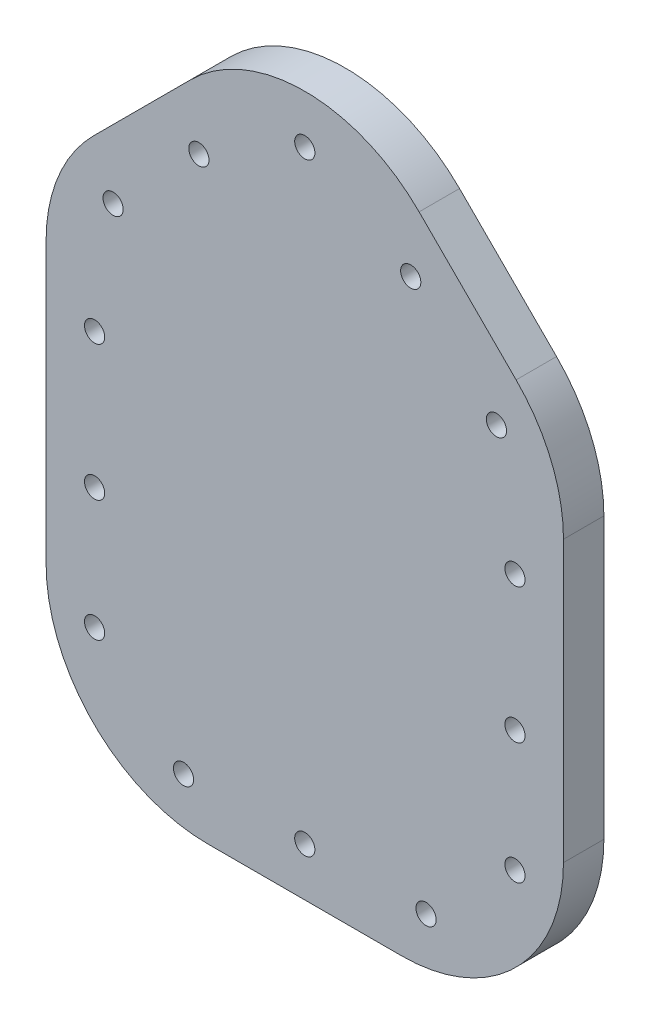
SolidWorks part; units mm, degrees
ref_plane "Front Plane" through (0, 0, 0) normal (0, 0, 1) x (1, 0, 0)
ref_plane "Top Plane" through (0, 0, 0) normal (0, 1, 0) x (1, 0, 0)
ref_plane "Right Plane" through (0, 0, 0) normal (1, 0, 0) x (0, 0, -1)
sketch "Sketch1" plane through (0, 0, 0) normal (0, 0, 1) x (1, 0, 0)
  line L0 (0, 107) -> (0, 0) construction
  line L1 (0, 107) -> (-37, 70) construction
  line L2 (-37, 70) -> (-37, 0) construction
  line L3 (-37, 0) -> (37, 0) construction
  line L4 (37, 70) -> (37, 0) construction
  line L5 (0, 107) -> (37, 70) construction
  line L6 (32, 5) -> (-32, 5)
  line L7 (-32, 5) -> (-32, 59.6447)
  line L8 (-26.1421, 73.7868) -> (-14.1421, 85.7868)
  line L9 (32, 5) -> (32, 59.6447)
  line L10 (26.1421, 73.7868) -> (14.1421, 85.7868)
  line L11 (0, 85.6447) -> (-5.799, 85.6447) construction
  line L12 (-5.799, 85.6447) -> (-26, 65.4437) construction
  line L13 (-26, 65.4437) -> (-26, 11) construction
  line L14 (-26, 11) -> (0, 11) construction
  arc A0 (14.1421, 85.7868) -> (-14.1421, 85.7868) centre (0, 71.6447) ccw
  arc A1 (-26.1421, 73.7868) -> (-32, 59.6447) centre (-12, 59.6447) ccw
  arc A2 (32, 59.6447) -> (26.1421, 73.7868) centre (12, 59.6447) ccw
  circle A3 centre (0, 85.6447) radius 1.25
  circle A4 centre (-13.1021, 78.3416) radius 1.25
  circle A5 centre (-23.7087, 67.735) radius 1.25
  circle A6 centre (-26, 52.911) radius 1.25
  circle A7 centre (-26, 36.198) radius 1.25
  circle A8 centre (-26, 21.198) radius 1.25
  circle A9 centre (0, 11) radius 1.25
  circle A10 centre (-15, 11) radius 1.25
  arc A11 (-32, 20) -> (-17, 5) centre (-17, 20) ccw construction
  circle A12 centre (13.1021, 78.3416) radius 1.25
  circle A13 centre (23.7087, 67.735) radius 1.25
  circle A14 centre (26, 52.911) radius 1.25
  circle A15 centre (26, 36.198) radius 1.25
  circle A16 centre (26, 21.198) radius 1.25
  circle A17 centre (15, 11) radius 1.25
  point P13 (0, 5)
  point P16 (0, 99.9289)
  point P19 (-32, 67.9289)
  point P22 (32, 67.9289)
  dimension "D7" = 20
  dimension "D8" = 20
  dimension "D9" = 20
  dimension "D10" = 6
  dimension "D14" = 2.5
  dimension "D15" = 15
  dimension "D1" = 45
  dimension "D2" = 37
  dimension "D3" = 70
  dimension "D4" = 5
  dimension "D5" = 5
  dimension "D6" = 5
  dimension "D11" = 14
  dimension "D12" = 6
  dimension "D13" = 6
  dimension "D16" = 15
  dimension "D17" = 15
  dimension "D18" = 15
  dimension "D19" = 15
  dimension "D20" = 15
  dimension "D21" = 15
extrude "Boss-Extrude1" add sketch "Sketch1" along normal blind 5
fillet "Fillet1" radius 20 2 edges at (32, 5, 2.5) (-32, 5, 2.5)
